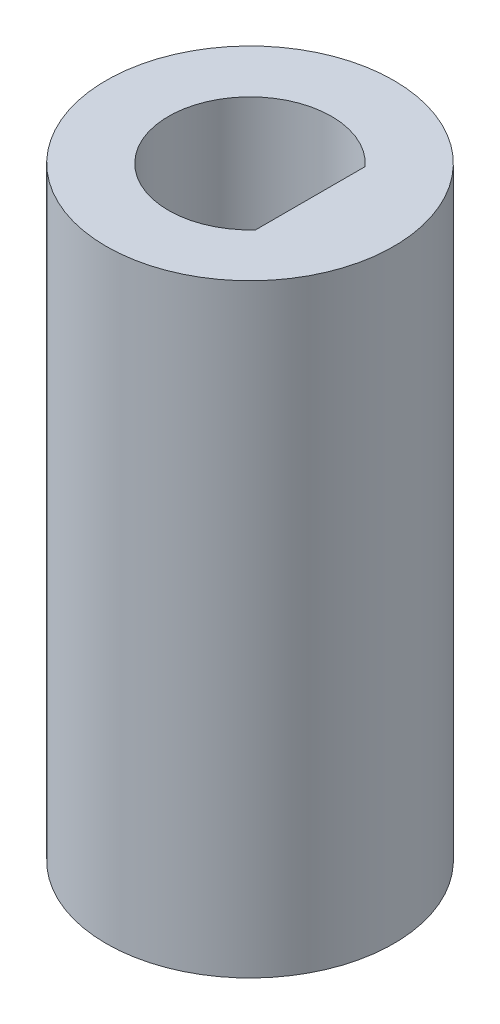
SolidWorks part; units mm, degrees
ref_plane "Front Plane" through (0, 0, 0) normal (0, 0, 1) x (1, 0, 0)
ref_plane "Top Plane" through (0, 0, 0) normal (0, 1, 0) x (1, 0, 0)
ref_plane "Right Plane" through (0, 0, 0) normal (1, 0, 0) x (0, 0, -1)
sketch "Sketch1" plane through (0, 0, 0) normal (0, 1, 0) x (1, 0, 0)
  line L0 (2, 1.8138) -> (2, -1.8138)
  arc A0 (2, 1.8138) -> (2, -1.8138) centre (0, 0) ccw
  circle A1 centre (0, 0) radius 4.7625
  dimension "D1" = 5.4
  dimension "D2" = 9.525
  dimension "D3" = 2
extrude "Boss-Extrude1" add sketch "Sketch1" along normal blind 20
